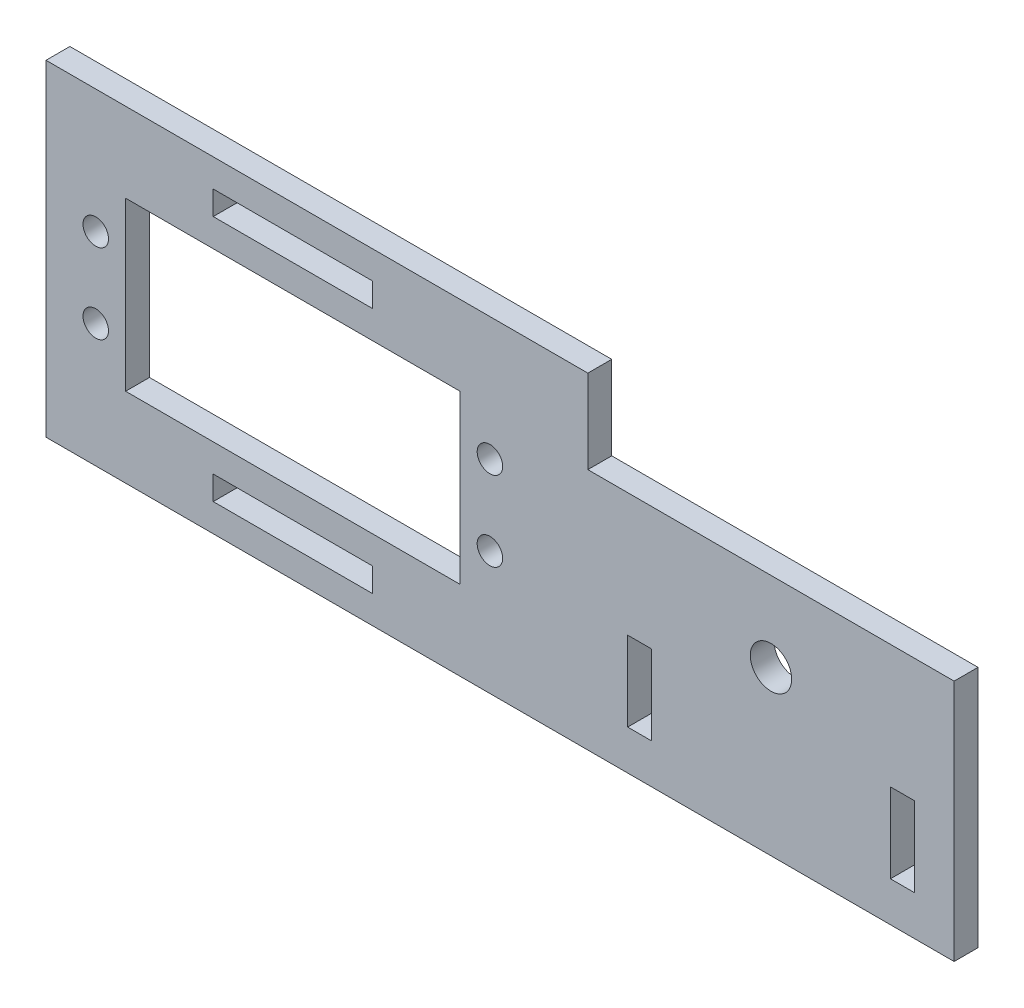
SolidWorks part; units mm, degrees
ref_plane "Plano frontal" through (0, 0, 0) normal (0, 0, 1) x (1, 0, 0)
ref_plane "Plano superior" through (0, 0, 0) normal (0, 1, 0) x (1, 0, 0)
ref_plane "Plano direito" through (0, 0, 0) normal (1, 0, 0) x (0, 0, -1)
sketch "Esboço1" plane through (0, 0, 0) normal (0, 0, 1) x (1, 0, 0)
  line L0 (0, 20.5) -> (0, 0) construction
  line L5 (15, 15) -> (18, 15)
  line L6 (18, 5) -> (18, 15)
  line L15 (10, 20.5) -> (-10, 20.5) construction
  line L16 (15, 5) -> (18, 5)
  line L21 (-15, 5) -> (-18, 5)
  line L22 (-15, 5) -> (-15, 15)
  line L27 (-15, 15) -> (-18, 15)
  line L28 (-18, 5) -> (-18, 15)
  line L29 (-15, 5) -> (-18, 15) construction
  line L30 (-15, 15) -> (-18, 5) construction
  line L35 (15, 5) -> (15, 15)
  line L36 (23, 0) -> (23, 30.5)
  line L37 (23, 30.5) -> (-23, 30.5)
  line L43 (-23, 0) -> (23, 0)
  line L49 (-23, 0) -> (-91.05, 0)
  line L50 (-91.05, 0) -> (-91.05, 41)
  line L55 (-91.05, 41) -> (-23, 41)
  line L56 (-23, 41) -> (-23, 30.5)
  line L61 (-60.05, 20.5) -> (-60.05, 0) construction
  line L62 (-81.05, 10) -> (-39.05, 10)
  line L63 (-81.05, 10) -> (-81.05, 31)
  line L64 (-81.05, 31) -> (-39.05, 31)
  line L65 (-39.05, 10) -> (-39.05, 31)
  line L66 (-81.05, 10) -> (-39.05, 31) construction
  line L67 (-81.05, 31) -> (-39.05, 10) construction
  line L68 (-60.05, 20.5) -> (-91.05, 20.5) construction
  line L69 (-60.05, 31) -> (-60.05, 41) construction
  line L70 (-50.05, 37.5) -> (-70.05, 37.5)
  line L71 (-50.05, 37.5) -> (-50.05, 34.5)
  line L72 (-50.05, 34.5) -> (-70.05, 34.5)
  line L73 (-70.05, 37.5) -> (-70.05, 34.5)
  line L74 (-50.05, 37.5) -> (-70.05, 34.5) construction
  line L75 (-50.05, 34.5) -> (-70.05, 37.5) construction
  line L76 (-50.05, 6.5) -> (-70.05, 6.5)
  line L77 (-70.05, 3.5) -> (-70.05, 6.5)
  line L78 (-50.05, 3.5) -> (-70.05, 3.5)
  line L79 (-50.05, 3.5) -> (-50.05, 6.5)
  circle A0 centre (0, 20.5) radius 2.6
  circle A1 centre (10, 20.5) radius 1.6 construction
  circle A2 centre (-10, 20.5) radius 1.6 construction
  circle A3 centre (-84.8, 15.5) radius 1.6
  circle A5 centre (-84.8, 25.5) radius 1.6
  circle A6 centre (-35.3, 25.5) radius 1.6
  circle A7 centre (-35.3, 15.5) radius 1.6
  point P0 (0, 20.5)
  point P12 (2.0255, 1.6198)
  point P13 (-16.5, 10)
  point P24 (-60.05, 20.5)
  point P26 (-16.5, 5.864)
  point P43 (-50, 20.5)
  point P44 (-60.05, 36)
  point P49 (0, 30.5)
  point P50 (23, 27.0347)
  point P57 (0, 0)
  point P58 (0, 0)
  point P59 (0, 0)
  point P60 (0, 0)
  dimension "D1" = 5.2
  dimension "D3" = 3.2
  dimension "D11" = 10
  dimension "D12" = 49.5
  dimension "D2" = 20
  dimension "D4" = 5
  dimension "D5" = 10
  dimension "D6" = 10
  dimension "D7" = 3
  dimension "D8" = 42
  dimension "D9" = 21
  dimension "D10" = 10
  dimension "D13" = 14.7
  dimension "D14" = 50
  dimension "D15" = 3
  dimension "D16" = 20
  dimension "D17" = 5
  dimension "D18" = 5
  dimension "D19" = 10
extrude "Ressalto-extrusão1" add sketch "Esboço1" along normal blind 3
